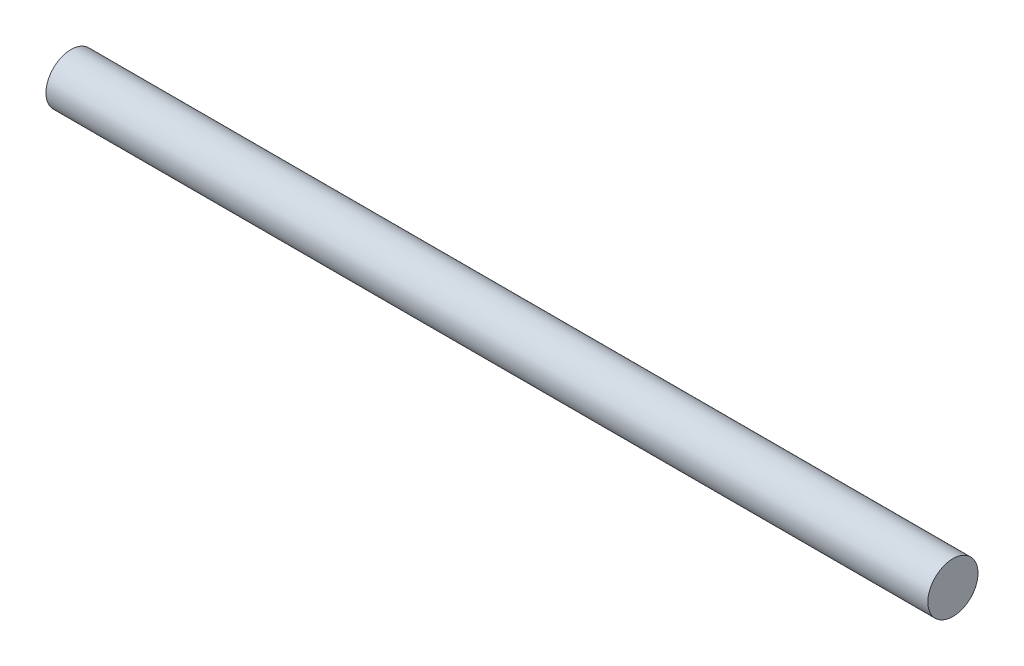
SolidWorks part; units mm, degrees
ref_plane "Alzado" through (0, 0, 0) normal (0, 0, 1) x (1, 0, 0)
ref_plane "Planta" through (0, 0, 0) normal (0, 1, 0) x (1, 0, 0)
ref_plane "Vista lateral" through (0, 0, 0) normal (1, 0, 0) x (0, 0, -1)
sketch "Croquis1" plane through (0, 0, 0) normal (1, 0, 0) x (0, 0, -1)
  circle A0 centre (0, 0) radius 2.5
  dimension "D1" = 5
extrude "Saliente-Extruir1" add sketch "Croquis1" along normal blind 87.9
